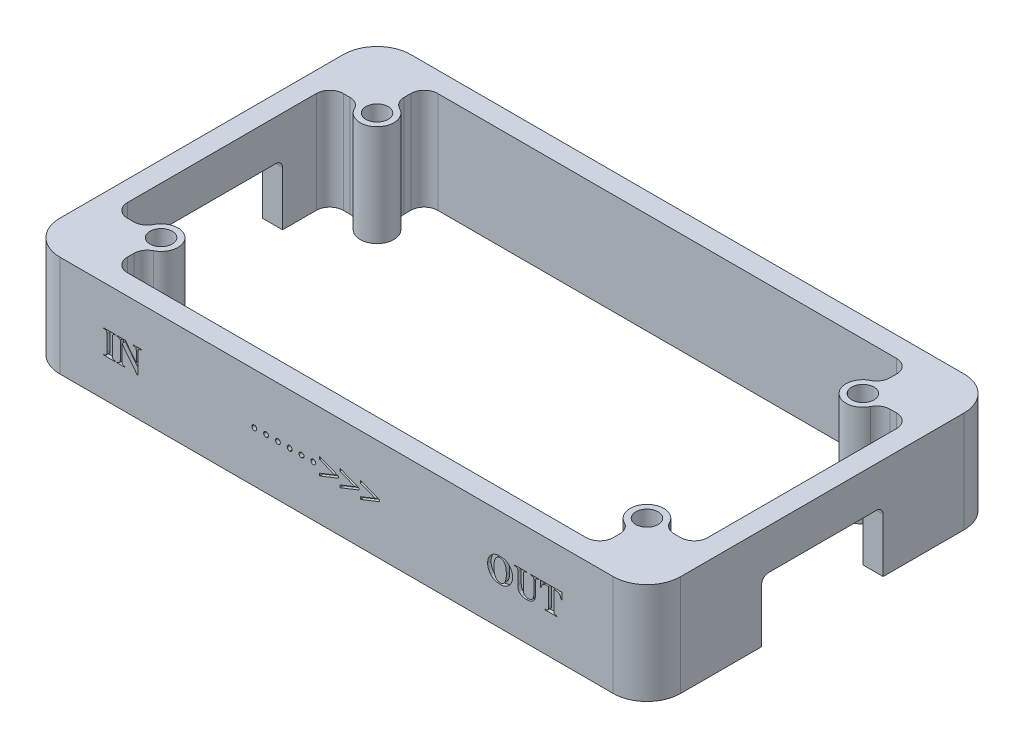
SolidWorks part; units mm, degrees
material "ABS"
ref_plane "前视基准面" through (0, 0, 0) normal (0, 0, 1) x (1, 0, 0)
ref_plane "上视基准面" through (0, 0, 0) normal (0, 1, 0) x (1, 0, 0)
ref_plane "右视基准面" through (0, 0, 0) normal (1, 0, 0) x (0, 0, -1)
other "Configuration Table"
sketch "草图1" plane through (0, 0, 0) normal (0, 1, 0) x (1, 0, 0)
  line L0 (-46, 26) -> (-46, -26)
  line L1 (-43, 23) -> (43, 23)
  line L2 (-43, 23) -> (-43, -23)
  line L3 (-43, -23) -> (43, -23)
  line L4 (43, 23) -> (43, -23)
  line L5 (-43, 23) -> (43, -23) construction
  line L6 (-43, -23) -> (43, 23) construction
  line L7 (-46, -26) -> (46, -26)
  line L8 (46, 26) -> (46, -26)
  line L9 (-46, 26) -> (46, 26)
  point P0 (0, 0)
  dimension "D1" = 46
  dimension "D2" = 86
  dimension "D3" = 3
extrude "凸台-拉伸1" add sketch "草图1" along normal blind 15
sketch "草图2" plane through (0, 0, 0) normal (0, -1, 0) x (1, 0, 0)
  line L0 (-38.5, 16) -> (-43, 16)
  line L1 (-36, 16) -> (36, 16) construction
  line L2 (-36, 16) -> (-36, -16) construction
  line L3 (-36, -16) -> (36, -16) construction
  line L4 (36, 16) -> (36, -16) construction
  line L5 (-36, 16) -> (36, -16) construction
  line L6 (-36, -16) -> (36, 16) construction
  line L7 (-43, -23) -> (-43, 23) construction
  line L8 (-36, 16) -> (-36, 17.65)
  line L9 (-43, 23) -> (43, 23) construction
  line L10 (-38.5, -16) -> (-43, -16)
  line L11 (-36, -18.5) -> (-36, -23)
  line L12 (43, -23) -> (-43, -23) construction
  line L13 (36, -18.5) -> (36, -23)
  line L14 (38.5, -16) -> (43, -16)
  line L15 (43, 23) -> (43, -23) construction
  line L16 (36, 18.5) -> (36, 23)
  line L17 (38.5, 16) -> (43, 16)
  line L18 (43, 23) -> (43, 16)
  line L19 (43, -23) -> (36, -23)
  line L20 (-43, -23) -> (-43, -16)
  line L21 (-43, 23) -> (-36, 23)
  line L22 (36, 23) -> (43, 23)
  line L23 (-43, 16) -> (-43, 23)
  line L24 (-36, -23) -> (-43, -23)
  line L25 (43, -16) -> (43, -23)
  line L26 (-36, 18.5) -> (-36, 23)
  arc A0 (-38.5, 16) -> (-36, 18.5) centre (-36, 16) ccw
  arc A1 (36, 18.5) -> (38.5, 16) centre (36, 16) ccw
  arc A2 (38.5, -16) -> (36, -18.5) centre (36, -16) ccw
  arc A3 (-36, -18.5) -> (-38.5, -16) centre (-36, -16) ccw
  circle A4 centre (-36, -16) radius 1.65
  circle A5 centre (36, -16) radius 1.65
  circle A6 centre (36, 16) radius 1.65
  circle A7 centre (-36, 16) radius 1.65
  point P0 (0, 0)
  line M5 (-43, 23) -> (43, 23)
  line M6 (43, 23) -> (43, -23)
  line M7 (43, -23) -> (-43, -23)
  line M8 (-43, -23) -> (-43, 23)
  dimension "D3" = 5
  dimension "D4" = 3.3
  dimension "D1" = 32
  dimension "D2" = 72
extrude "凸台-拉伸3" add sketch "草图2" against normal up to surface (15 mm away) contours L16 A1 L17 A6 M6 M5 | L14 A2 L13 A5 M7 M6 | L11 A3 L10 A4 M8 M7 | L0 A0 L26 A7 M5 M8 up to face at (0, 15, 0)
sketch "草图3" plane through (46, 0, 0) normal (1, 0, 0) x (0, 0, -1)
  line L1 (-9, -9) -> (9, -9)
  line L2 (-9, -9) -> (-9, 9)
  line L3 (-9, 9) -> (9, 9)
  line L4 (9, -9) -> (9, 9)
  line L5 (-9, -9) -> (9, 9) construction
  line L6 (-9, 9) -> (9, -9) construction
  point P0 (0, 0)
  dimension "D1" = 18
  dimension "D2" = 18
extrude "切除-拉伸1" cut sketch "草图3" against normal through all both and the other way through all
fillet "圆角1" radius 2 16 edges at (38.5, 7.5, 16) (43, 7.5, 16) (43, 7.5, -16) (38.5, 7.5, -16) (36, 7.5, -18.5) (36, 7.5, -23) (-36, 7.5, -23) (-36, 7.5, -18.5) (-38.5, 7.5, -16) (-43, 7.5, -16) (-43, 7.5, 16) (-38.5, 7.5, 16) (-36, 7.5, 18.5) (-36, 7.5, 23) (36, 7.5, 23) (36, 7.5, 18.5)
fillet "圆角2" radius 5 4 edges at (-46, 7.5, 26) (46, 7.5, 26) (46, 7.5, -26) (-46, 7.5, -26)
fillet "圆角3" radius 1 4 edges at (44.5, 9, -9) (44.5, 9, 9) (-44.5, 9, 9) (-44.5, 9, -9)
sketch "草图4" plane through (0, 0, 26) normal (0, 0, 1) x (1, 0, 0)
  text T0 "<b>IN            ······>>>            OUT</b>" font "Times New Roman" height 3.5
extrude "切除-拉伸2" cut sketch "草图4" against normal blind 0.5 and the other way through all
sketch "草图5" plane through (0, 0, -26) normal (0, 0, -1) x (-1, 0, 0)
  text T0 "<b>OUT            <<<······            IN</b>" font "Times New Roman" height 3.5
extrude "切除-拉伸3" cut sketch "草图5" against normal blind 0.5
